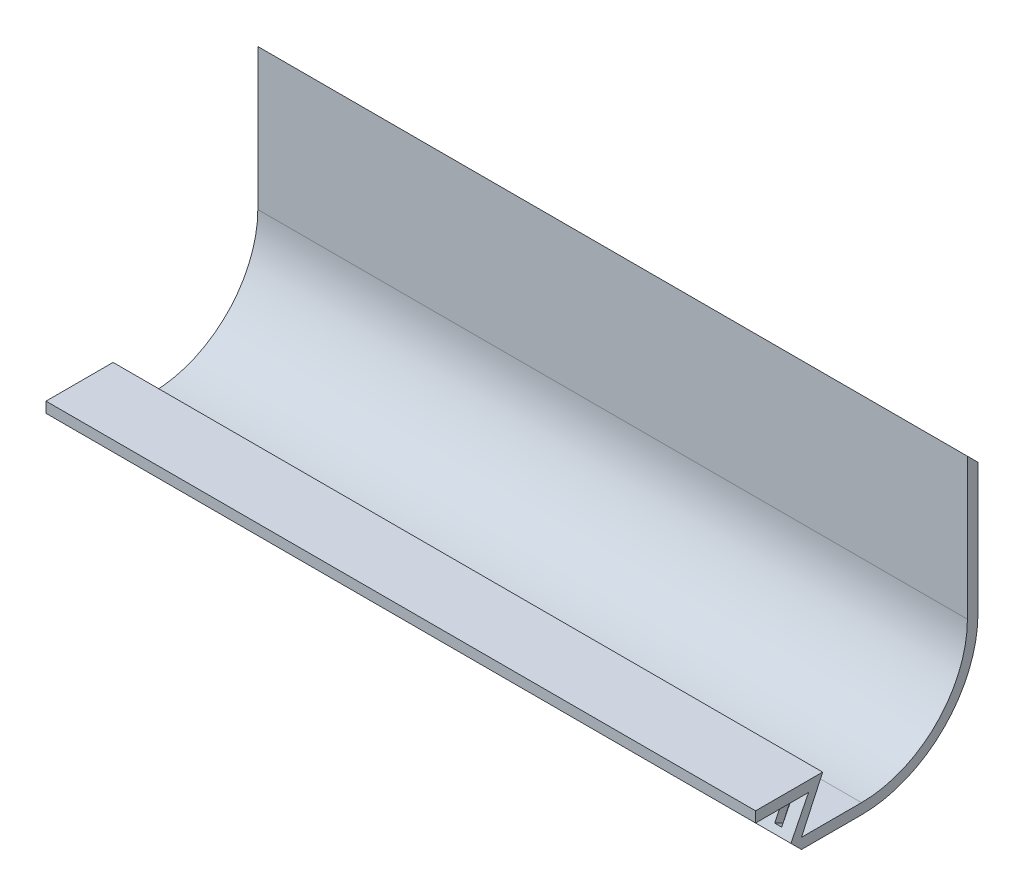
SolidWorks part; units mm, degrees
ref_plane "前视基准面" through (0, 0, 0) normal (0, 0, 1) x (1, 0, 0)
ref_plane "上视基准面" through (0, 0, 0) normal (0, 1, 0) x (1, 0, 0)
ref_plane "右视基准面" through (0, 0, 0) normal (1, 0, 0) x (0, 0, -1)
sketch "草图1" plane through (0, 0, 0) normal (0, 0, 1) x (1, 0, 0)
  line L61 (-143.75, 30) -> (-143.75, 70)
  line L65 (-135.75, 30) -> (-143.75, 30)
  line L80 (-105.75, 65) -> (-105.75, 70)
  line L81 (-143.75, 70) -> (-105.75, 70)
  line L82 (-105.75, 65) -> (-100.25, 65)
  line L83 (-100.25, 65) -> (-100.25, 70)
  line L84 (-100.25, 70) -> (99.75, 70)
  line L85 (-135.75, 30) -> (-135.75, -30)
  line L87 (143.25, -30) -> (143.25, -70)
  line L89 (99.75, 65) -> (99.75, 70)
  line L90 (105.25, 65) -> (99.75, 65)
  line L92 (105.25, 65) -> (105.25, 70)
  line L96 (105.25, -65) -> (105.25, -70)
  line L97 (143.25, -70) -> (105.25, -70)
  line L98 (105.25, -65) -> (99.75, -65)
  line L99 (99.75, -65) -> (99.75, -70)
  line L100 (-100.25, -70) -> (99.75, -70)
  line L101 (-100.25, -65) -> (-100.25, -70)
  line L102 (-105.75, -65) -> (-100.25, -65)
  line L103 (-143.75, -70) -> (-105.75, -70)
  line L104 (-105.75, -65) -> (-105.75, -70)
  line L105 (-135.75, -30) -> (-143.75, -30)
  line L106 (-143.75, -30) -> (-143.75, -70)
  line L107 (143.25, 30) -> (143.25, 70)
  line L108 (105.25, 70) -> (143.25, 70)
  line L109 (143.25, 30) -> (135.25, 30)
  line L110 (135.25, 30) -> (135.25, -30)
  line L111 (135.25, -30) -> (143.25, -30)
  point P9 (-0.25, 70)
  point P27 (-135.75, 0)
  point P35 (0, -70)
extrude "凸台-拉伸1" add sketch "草图1" along normal blind 3
ref_plane "基准面1" through (-143.75, 0, 0) normal (-1, 0, 0) x (0, 0, 1)
sketch "草图2" plane through (-143.75, 0, 0) normal (-1, 0, 0) x (0, 0, 1)
  line L1 (0, 70) -> (0, 30)
  line L2 (0, 30) -> (-3, 33)
  line L3 (-3, 33) -> (-3, 70)
  line L4 (50, 100) -> (47, 103)
  line L8 (30, 103) -> (47, 103)
  line L17 (45, 90) -> (50, 100)
  line L18 (45, 90) -> (60, 90)
  line L19 (60, 90) -> (60, 87)
  line L20 (60, 87) -> (41, 87)
  line L21 (41, 87) -> (47, 100)
  line L22 (30, 100) -> (47, 100)
  line L24 (30, -100) -> (47, -100)
  line L25 (41, -87) -> (47, -100)
  line L26 (60, -87) -> (41, -87)
  line L27 (60, -90) -> (60, -87)
  line L28 (45, -90) -> (60, -90)
  line L29 (45, -90) -> (50, -100)
  line L30 (30, -103) -> (47, -103)
  line L31 (50, -100) -> (47, -103)
  line L32 (-3, -33) -> (-3, -70)
  line L33 (0, -30) -> (-3, -33)
  line L34 (0, -70) -> (0, -30)
  arc A0 (0, 70) -> (30, 100) centre (30, 70) cw
  arc A1 (-3, 70) -> (30, 103) centre (30, 70) cw
  arc A4 (-3, -70) -> (30, -103) centre (30, -70) ccw
  arc A5 (0, -70) -> (30, -100) centre (30, -70) ccw
extrude "凸台-拉伸2" add sketch "草图2" against normal blind 287
ref_plane "基准面2" through (143.25, 0, 0) normal (1, 0, 0) x (0, 0, -1)
sketch "草图6" plane through (0, 0, 0) normal (0, 0, 1) x (1, 0, 0)
  line L1 (100.25, 103) -> (100.25, -126.9049)
  line L2 (100.25, 103) -> (173.8547, 103)
  line L3 (143.25, 103) -> (-143.75, 103) construction
  line L11 (100.25, -126.9049) -> (173.8547, -126.9049)
  line L12 (173.8547, 103) -> (173.8547, -126.9049)
  line L13 (-100.75, 103) -> (-258.1833, 103)
  line L15 (-100.75, -122.8) -> (-258.1833, -122.8)
  line L16 (-258.1833, 103) -> (-258.1833, -122.8)
  line L17 (-100.75, 103) -> (-100.75, -122.8)
extrude "切除-拉伸6" cut sketch "草图6" against normal blind 100 and the other way blind 100
sketch "草图7" plane through (143.25, 0, 0) normal (1, 0, 0) x (0, 0, -1)
  line L1 (-3, 70) -> (0, 70)
  line L2 (-3, 70) -> (-3, -70)
  line L3 (-3, -70) -> (0, -70)
  line L4 (0, 70) -> (0, -70)
extrude "切除-拉伸7" cut sketch "草图7" against normal through all
ref_plane "基准面3" through (0, 0, 0) normal (0, 0.4472, 0.8944) x (1, 0, 0)
sketch "草图8" plane through (0, 0, 0) normal (0, 0.4472, 0.8944) x (1, 0, 0)
  line L0 (-97.25, -109.8034) -> (-95.25, -109.8034)
  line L2 (-97.25, -109.8034) -> (-97.25, -99.8034)
  line L7 (-97.25, -99.8034) -> (-95.25, -99.8034)
  line L8 (-95.25, -109.8034) -> (-95.25, -99.8034)
  line L9 (-91.25, -109.8034) -> (-89.25, -109.8034)
  line L10 (-91.25, -109.8034) -> (-91.25, -99.8034)
  line L11 (-91.25, -99.8034) -> (-89.25, -99.8034)
  line L12 (-89.25, -109.8034) -> (-89.25, -99.8034)
  line L13 (-85.25, -109.8034) -> (-83.25, -109.8034)
  line L14 (-85.25, -109.8034) -> (-85.25, -99.8034)
  line L15 (-85.25, -99.8034) -> (-83.25, -99.8034)
  line L16 (-83.25, -109.8034) -> (-83.25, -99.8034)
  line L17 (-79.25, -109.8034) -> (-77.25, -109.8034)
  line L18 (-79.25, -109.8034) -> (-79.25, -99.8034)
  line L19 (-79.25, -99.8034) -> (-77.25, -99.8034)
  line L20 (-77.25, -109.8034) -> (-77.25, -99.8034)
  line L21 (-73.25, -109.8034) -> (-71.25, -109.8034)
  line L22 (-73.25, -109.8034) -> (-73.25, -99.8034)
  line L23 (-73.25, -99.8034) -> (-71.25, -99.8034)
  line L24 (-71.25, -109.8034) -> (-71.25, -99.8034)
  line L25 (-67.25, -109.8034) -> (-65.25, -109.8034)
  line L26 (-67.25, -109.8034) -> (-67.25, -99.8034)
  line L27 (-67.25, -99.8034) -> (-65.25, -99.8034)
  line L28 (-65.25, -109.8034) -> (-65.25, -99.8034)
  line L29 (-61.25, -109.8034) -> (-59.25, -109.8034)
  line L30 (-61.25, -109.8034) -> (-61.25, -99.8034)
  line L31 (-61.25, -99.8034) -> (-59.25, -99.8034)
  line L32 (-59.25, -109.8034) -> (-59.25, -99.8034)
  line L33 (-55.25, -109.8034) -> (-53.25, -109.8034)
  line L34 (-55.25, -109.8034) -> (-55.25, -99.8034)
  line L35 (-55.25, -99.8034) -> (-53.25, -99.8034)
  line L36 (-53.25, -109.8034) -> (-53.25, -99.8034)
  line L37 (-49.25, -109.8034) -> (-47.25, -109.8034)
  line L38 (-49.25, -109.8034) -> (-49.25, -99.8034)
  line L39 (-49.25, -99.8034) -> (-47.25, -99.8034)
  line L40 (-47.25, -109.8034) -> (-47.25, -99.8034)
  line L41 (-43.25, -109.8034) -> (-41.25, -109.8034)
  line L42 (-43.25, -109.8034) -> (-43.25, -99.8034)
  line L43 (-43.25, -99.8034) -> (-41.25, -99.8034)
  line L44 (-41.25, -109.8034) -> (-41.25, -99.8034)
  line L45 (-37.25, -109.8034) -> (-35.25, -109.8034)
  line L46 (-37.25, -109.8034) -> (-37.25, -99.8034)
  line L47 (-37.25, -99.8034) -> (-35.25, -99.8034)
  line L48 (-35.25, -109.8034) -> (-35.25, -99.8034)
  line L49 (-31.25, -109.8034) -> (-29.25, -109.8034)
  line L50 (-31.25, -109.8034) -> (-31.25, -99.8034)
  line L51 (-31.25, -99.8034) -> (-29.25, -99.8034)
  line L52 (-29.25, -109.8034) -> (-29.25, -99.8034)
  line L53 (-25.25, -109.8034) -> (-23.25, -109.8034)
  line L54 (-25.25, -109.8034) -> (-25.25, -99.8034)
  line L55 (-25.25, -99.8034) -> (-23.25, -99.8034)
  line L56 (-23.25, -109.8034) -> (-23.25, -99.8034)
  line L57 (-19.25, -109.8034) -> (-17.25, -109.8034)
  line L58 (-19.25, -109.8034) -> (-19.25, -99.8034)
  line L59 (-19.25, -99.8034) -> (-17.25, -99.8034)
  line L60 (-17.25, -109.8034) -> (-17.25, -99.8034)
  line L61 (-13.25, -109.8034) -> (-11.25, -109.8034)
  line L62 (-13.25, -109.8034) -> (-13.25, -99.8034)
  line L63 (-13.25, -99.8034) -> (-11.25, -99.8034)
  line L64 (-11.25, -109.8034) -> (-11.25, -99.8034)
  line L65 (-7.25, -109.8034) -> (-5.25, -109.8034)
  line L66 (-7.25, -109.8034) -> (-7.25, -99.8034)
  line L67 (-7.25, -99.8034) -> (-5.25, -99.8034)
  line L68 (-5.25, -109.8034) -> (-5.25, -99.8034)
  line L69 (-1.25, -109.8034) -> (0.75, -109.8034)
  line L70 (-1.25, -109.8034) -> (-1.25, -99.8034)
  line L71 (-1.25, -99.8034) -> (0.75, -99.8034)
  line L72 (0.75, -109.8034) -> (0.75, -99.8034)
  line L73 (4.75, -109.8034) -> (6.75, -109.8034)
  line L74 (4.75, -109.8034) -> (4.75, -99.8034)
  line L75 (4.75, -99.8034) -> (6.75, -99.8034)
  line L76 (6.75, -109.8034) -> (6.75, -99.8034)
  line L77 (10.75, -109.8034) -> (12.75, -109.8034)
  line L78 (10.75, -109.8034) -> (10.75, -99.8034)
  line L79 (10.75, -99.8034) -> (12.75, -99.8034)
  line L80 (12.75, -109.8034) -> (12.75, -99.8034)
  line L81 (16.75, -109.8034) -> (18.75, -109.8034)
  line L82 (16.75, -109.8034) -> (16.75, -99.8034)
  line L83 (16.75, -99.8034) -> (18.75, -99.8034)
  line L84 (18.75, -109.8034) -> (18.75, -99.8034)
  line L85 (22.75, -109.8034) -> (24.75, -109.8034)
  line L86 (22.75, -109.8034) -> (22.75, -99.8034)
  line L87 (22.75, -99.8034) -> (24.75, -99.8034)
  line L88 (24.75, -109.8034) -> (24.75, -99.8034)
  line L89 (28.75, -109.8034) -> (30.75, -109.8034)
  line L90 (28.75, -109.8034) -> (28.75, -99.8034)
  line L91 (28.75, -99.8034) -> (30.75, -99.8034)
  line L92 (30.75, -109.8034) -> (30.75, -99.8034)
  line L93 (34.75, -109.8034) -> (36.75, -109.8034)
  line L94 (34.75, -109.8034) -> (34.75, -99.8034)
  line L95 (34.75, -99.8034) -> (36.75, -99.8034)
  line L96 (36.75, -109.8034) -> (36.75, -99.8034)
  line L97 (40.75, -109.8034) -> (42.75, -109.8034)
  line L98 (40.75, -109.8034) -> (40.75, -99.8034)
  line L99 (40.75, -99.8034) -> (42.75, -99.8034)
  line L100 (42.75, -109.8034) -> (42.75, -99.8034)
  line L101 (46.75, -109.8034) -> (48.75, -109.8034)
  line L102 (46.75, -109.8034) -> (46.75, -99.8034)
  line L103 (46.75, -99.8034) -> (48.75, -99.8034)
  line L104 (48.75, -109.8034) -> (48.75, -99.8034)
  line L105 (52.75, -109.8034) -> (54.75, -109.8034)
  line L106 (52.75, -109.8034) -> (52.75, -99.8034)
  line L107 (52.75, -99.8034) -> (54.75, -99.8034)
  line L108 (54.75, -109.8034) -> (54.75, -99.8034)
  line L109 (58.75, -109.8034) -> (60.75, -109.8034)
  line L110 (58.75, -109.8034) -> (58.75, -99.8034)
  line L111 (58.75, -99.8034) -> (60.75, -99.8034)
  line L112 (60.75, -109.8034) -> (60.75, -99.8034)
  line L113 (64.75, -109.8034) -> (66.75, -109.8034)
  line L114 (64.75, -109.8034) -> (64.75, -99.8034)
  line L115 (64.75, -99.8034) -> (66.75, -99.8034)
  line L116 (66.75, -109.8034) -> (66.75, -99.8034)
  line L117 (70.75, -109.8034) -> (72.75, -109.8034)
  line L118 (70.75, -109.8034) -> (70.75, -99.8034)
  line L119 (70.75, -99.8034) -> (72.75, -99.8034)
  line L120 (72.75, -109.8034) -> (72.75, -99.8034)
  line L121 (76.75, -109.8034) -> (78.75, -109.8034)
  line L122 (76.75, -109.8034) -> (76.75, -99.8034)
  line L123 (76.75, -99.8034) -> (78.75, -99.8034)
  line L124 (78.75, -109.8034) -> (78.75, -99.8034)
  line L125 (82.75, -109.8034) -> (84.75, -109.8034)
  line L126 (82.75, -109.8034) -> (82.75, -99.8034)
  line L127 (82.75, -99.8034) -> (84.75, -99.8034)
  line L128 (84.75, -109.8034) -> (84.75, -99.8034)
  line L129 (88.75, -109.8034) -> (90.75, -109.8034)
  line L130 (88.75, -109.8034) -> (88.75, -99.8034)
  line L131 (88.75, -99.8034) -> (90.75, -99.8034)
  line L132 (90.75, -109.8034) -> (90.75, -99.8034)
  line L133 (94.75, -109.8034) -> (96.75, -109.8034)
  line L134 (94.75, -109.8034) -> (94.75, -99.8034)
  line L135 (94.75, -99.8034) -> (96.75, -99.8034)
  line L136 (96.75, -109.8034) -> (96.75, -99.8034)
extrude "切除-拉伸8" cut sketch "草图8" against normal up to next
